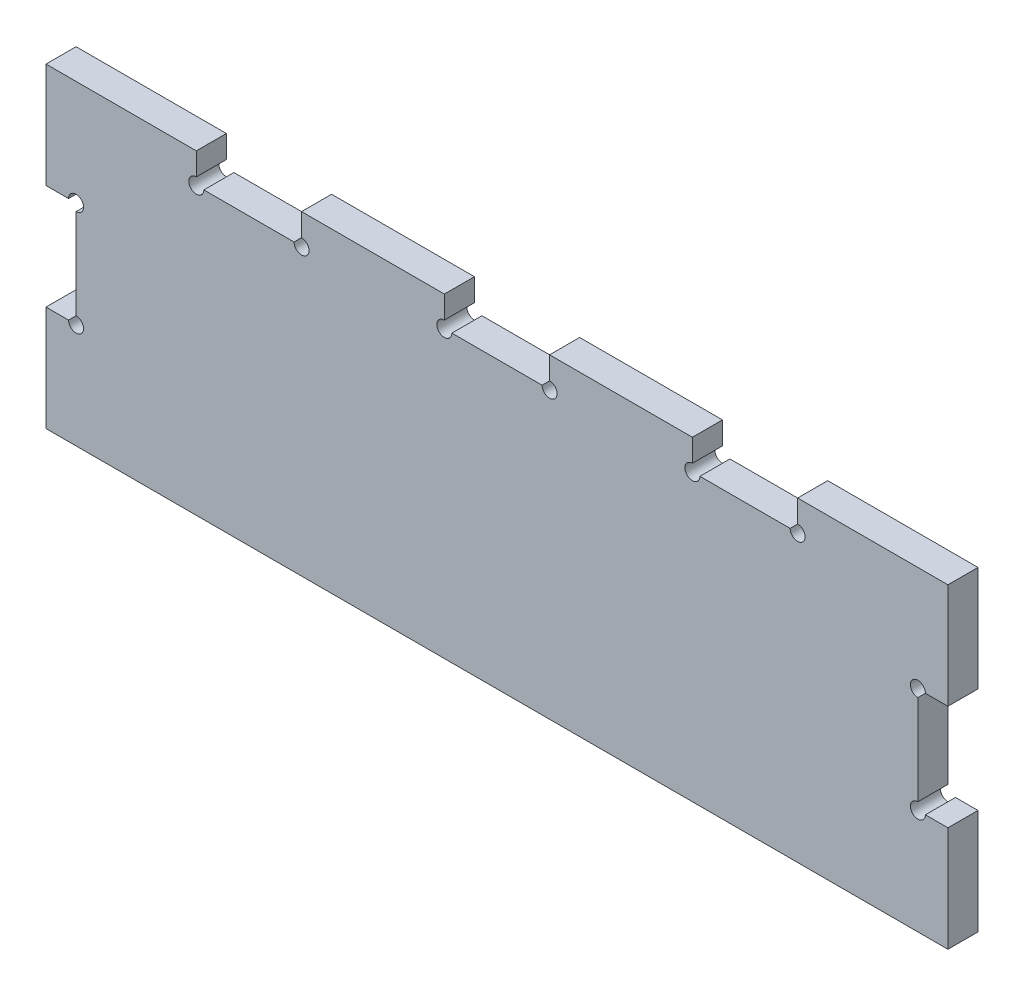
SolidWorks part; units mm, degrees
ref_plane "Front" through (0, 0, 0) normal (0, 0, 1) x (1, 0, 0)
ref_plane "Top" through (0, 0, 0) normal (0, 1, 0) x (1, 0, 0)
ref_plane "Right" through (0, 0, 0) normal (1, 0, 0) x (0, 0, -1)
sketch "草图1" plane through (0, 0, 0) normal (0, 0, 1) x (1, 0, 0)
  line L1 (0, 0) -> (60, 0)
  line L2 (0, 0) -> (0, 21)
  line L3 (0, 21) -> (60, 21)
  line L4 (60, 0) -> (60, 21)
  dimension "D1" = 21
  dimension "D2" = 60
extrude "凸台-拉伸1" add sketch "草图1" along normal blind 2
sketch "草图2" plane through (0, 0, 2) normal (0, 0, 1) x (1, 0, 0)
  line L0 (0, 21) -> (0, 0) construction
  line L1 (0, 14) -> (2, 14)
  line L2 (0, 14) -> (0, 7)
  line L3 (0, 7) -> (2, 7)
  line L4 (2, 14) -> (2, 7)
  line L5 (60, 21) -> (0, 21) construction
  line L6 (60, 0) -> (60, 21) construction
  line L7 (60, 14) -> (58, 14)
  line L8 (60, 14) -> (60, 7)
  line L9 (60, 7) -> (58, 7)
  line L10 (58, 14) -> (58, 7)
  dimension "D1" = 2
  dimension "D2" = 7
  dimension "D3" = 7
  dimension "D4" = 2
  dimension "D5" = 0
extrude "切除-拉伸1" cut sketch "草图2" against normal through all
sketch "草图3" plane through (0, 0, 2) normal (0, 0, 1) x (1, 0, 0)
  line L0 (60, 21) -> (0, 21) construction
  line L1 (10, 21) -> (17, 21)
  line L2 (10, 21) -> (10, 19)
  line L3 (10, 19) -> (17, 19)
  line L4 (17, 21) -> (17, 19)
  line L5 (0, 21) -> (0, 14) construction
  line L6 (60, 14) -> (60, 21) construction
  line L7 (26.5, 21) -> (33.5, 21)
  line L8 (26.5, 21) -> (26.5, 19)
  line L9 (26.5, 19) -> (33.5, 19)
  line L10 (33.5, 21) -> (33.5, 19)
  line L11 (43, 21) -> (50, 21)
  line L12 (43, 21) -> (43, 19)
  line L13 (43, 19) -> (50, 19)
  line L14 (50, 21) -> (50, 19)
  dimension "D1" = 7
  dimension "D2" = 2
  dimension "D3" = 10
  dimension "D4" = 7
  dimension "D5" = 7
  dimension "D6" = 2
  dimension "D7" = 2
  dimension "D8" = 10
  dimension "D9" = 9.5
extrude "切除-拉伸2" cut sketch "草图3" against normal through all
sketch "草图4" plane through (0, 0, 2) normal (0, 0, 1) x (1, 0, 0)
  point P0 (2, 14)
  point P1 (2, 7)
  point P3 (10, 19)
  point P5 (17, 19)
  point P7 (26.5, 19)
  point P9 (33.5, 19)
  point P11 (43, 19)
  point P13 (50, 19)
  point P15 (58, 14)
  point P17 (58, 7)
sketch "草图5" plane through (0, 0, 2) normal (0, 0, 1) x (1, 0, 0)
  circle A0 centre (2, 7) radius 0.5
extrude "切除-拉伸3" cut sketch "草图5" against normal through all
pattern_sketch "草图阵列1" of "切除-拉伸3" driven by "草图4"
